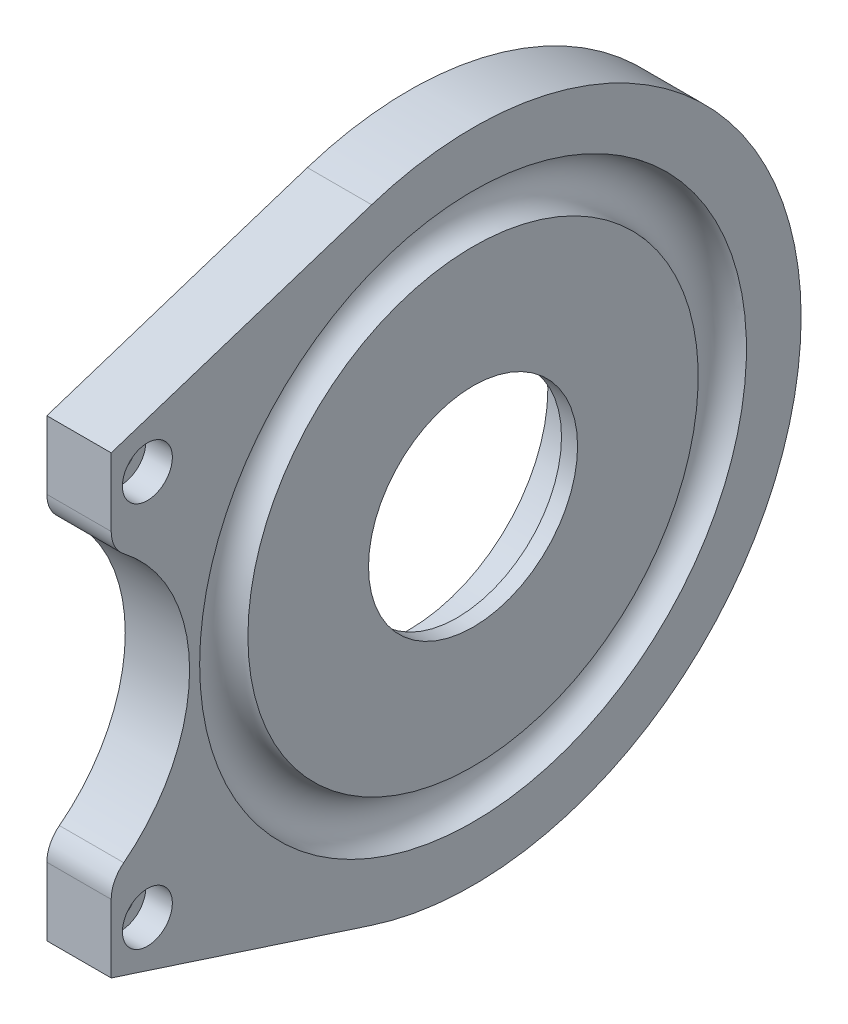
SolidWorks part; units mm, degrees
ref_plane "前视基准面" through (0, 0, 0) normal (0, 0, 1) x (1, 0, 0)
ref_plane "上视基准面" through (0, 0, 0) normal (0, 1, 0) x (1, 0, 0)
ref_plane "右视基准面" through (0, 0, 0) normal (1, 0, 0) x (0, 0, -1)
sketch "草图1" plane through (0, 0, 0) normal (1, 0, 0) x (0, 0, -1)
  line L0 (-45, -19.81) -> (-45, -28.2783)
  line L1 (-45, -28.2783) -> (-12.6079, -38.8031)
  line L2 (-12.6079, 38.8031) -> (-45, 28.2783)
  line L3 (-45, 28.2783) -> (-45, 19.81)
  circle A0 centre (0, 0) radius 28.0129 construction
  arc A1 (-43.44, -16.6404) -> (-43.44, 16.6404) centre (-56.25, 0) ccw
  arc A2 (-43.44, -16.6404) -> (-45, -19.81) centre (-41, -19.81) ccw
  arc A3 (-12.6079, -38.8031) -> (-12.6079, 38.8031) centre (0, 0) ccw
  arc A4 (-45, 19.81) -> (-43.44, 16.6404) centre (-41, 19.81) ccw
  dimension "D1" = 56.0259
  dimension "D2" = 40.8
  dimension "D3" = 4
  dimension "D4" = 4
  dimension "D9" = 21
  dimension "D5" = 32.3921
  dimension "D6" = 32.3921
  dimension "D7" = 8.4682
  dimension "D8" = 8.4682
  dimension "D10" = 77.6062
  dimension "D11" = 18.9931
  dimension "D12" = 11.6378
  dimension "D13" = 3.1696
  dimension "D14" = 18.9931
  dimension "D15" = 45
  dimension "D16" = 28.2783
extrude "凸台-拉伸1" add sketch "草图1" along normal blind 8
sketch "草图3" plane through (0, 0, 0) normal (0, 1, 0) x (1, 0, 0)
  line L0 (0, 0) -> (8, 0) construction
  line L1 (8, -12.6079) -> (8, 40.8) construction
  line L6 (8, 34) -> (8, 28)
  arc A0 (8, 34) -> (8, 28) centre (8, 31) ccw
  point P14 (8, 31)
  dimension "D1" = 3
revolve "切除-旋转1" cut sketch "草图3" angle 360 about L0
sketch "草图4" plane through (8, 0, 0) normal (1, 0, 0) x (0, 0, -1)
  line L1 (-45, -19.81) -> (-45, -28.2783) construction
  line L2 (0, 0) -> (-35.25, 0) construction
  circle A0 centre (-40.5, -23.9988) radius 3.105
  arc A1 (-43.44, -16.6404) -> (-43.44, 16.6404) centre (-56.25, 0) ccw construction
  circle A2 centre (-40.5, 23.9988) radius 3.105
  dimension "D3" = 6.21
  dimension "D1" = 4.5
extrude "切除-拉伸1" cut sketch "草图4" against normal blind 3.3
sketch "草图5" plane through (4.7, 0, 0) normal (1, 0, 0) x (0, 0, -1)
  line L0 (0, 0) -> (-56.25, 0) construction
  circle A0 centre (-40.5, -23.9988) radius 1.65
  circle A3 centre (-40.5, 23.9988) radius 1.65
  dimension "D2" = 3.3
extrude "切除-拉伸2" cut sketch "草图5" against normal through all
sketch "草图6" plane through (0, 0, 0) normal (-1, 0, 0) x (0, 0, 1)
  circle A1 centre (0, 0) radius 17.3
  dimension "D1" = 34.6
extrude "切除-拉伸3" cut sketch "草图6" against normal blind 6
sketch "草图7" plane through (6, 0, 0) normal (-1, 0, 0) x (0, 0, 1)
  circle A0 centre (0, 0) radius 13
extrude "切除-拉伸4" cut sketch "草图7" against normal through all
